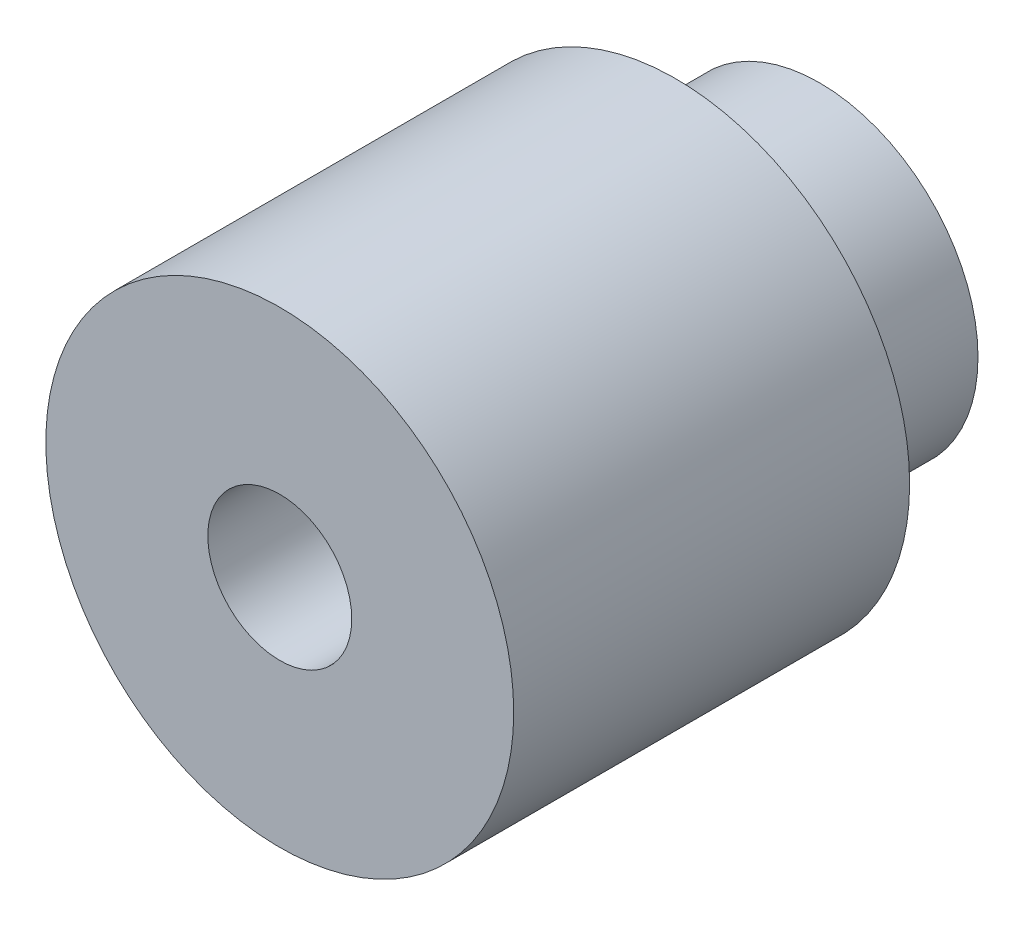
SolidWorks part; units mm, degrees
ref_plane "Front Plane" through (0, 0, 0) normal (0, 0, 1) x (1, 0, 0)
ref_plane "Top Plane" through (0, 0, 0) normal (0, 1, 0) x (1, 0, 0)
ref_plane "Right Plane" through (0, 0, 0) normal (1, 0, 0) x (0, 0, -1)
sketch "Sketch1" plane through (0, 0, 0) normal (0, 0, 1) x (1, 0, 0)
  circle A0 centre (0, 0) radius 4.4
  circle A1 centre (0, 0) radius 2
extrude "Rc 1/8 connection, thread core envelope" add sketch "Sketch1" along normal blind 4 from offset 4
sketch "Sketch2" plane through (0, 0, 0) normal (0, 0, 1) x (1, 0, 0)
  circle A0 centre (0, 0) radius 6.5
  circle A1 centre (0, 0) radius 2
extrude "Short fitting and tool access envelope" add sketch "Sketch2" along normal blind 11
